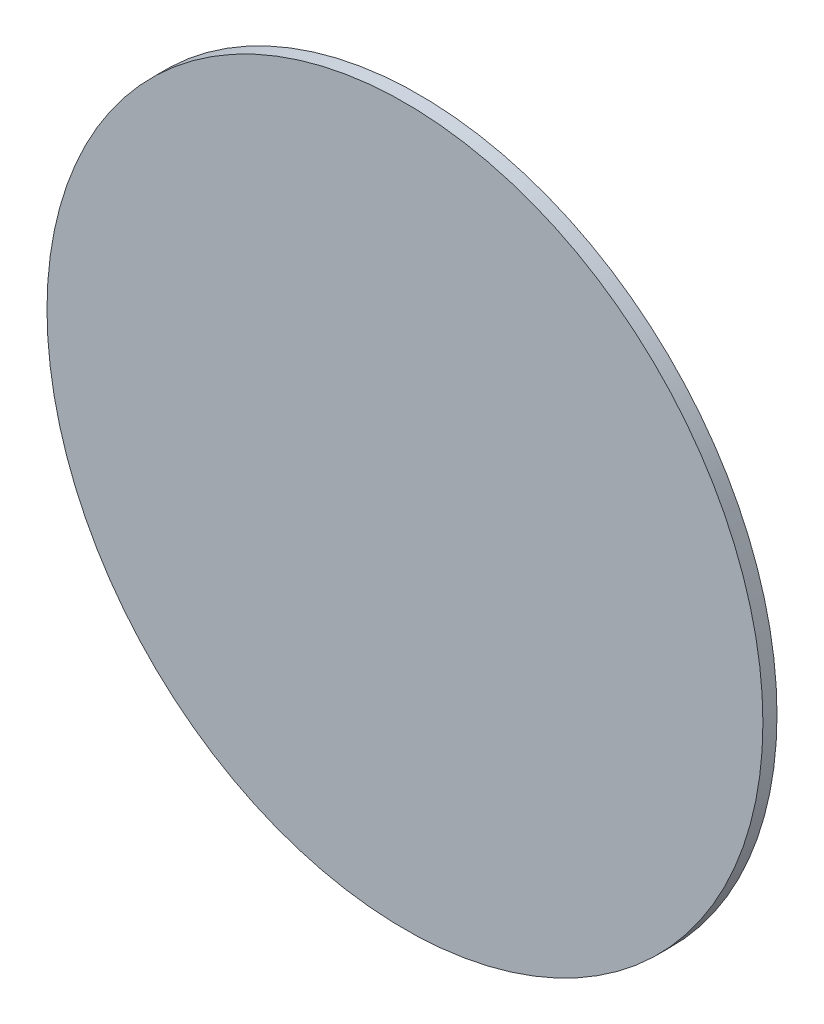
SolidWorks part; units mm, degrees
ref_plane "Front Plane" through (0, 0, 0) normal (0, 0, 1) x (1, 0, 0)
ref_plane "Top Plane" through (0, 0, 0) normal (0, 1, 0) x (1, 0, 0)
ref_plane "Right Plane" through (0, 0, 0) normal (1, 0, 0) x (0, 0, -1)
sketch "Sketch1" plane through (0, 0, 0) normal (0, 0, 1) x (1, 0, 0)
  circle A0 centre (0, 0) radius 25.4
  dimension "D1" = 50.8
extrude "Boss-Extrude1" add sketch "Sketch1" along normal blind 1
